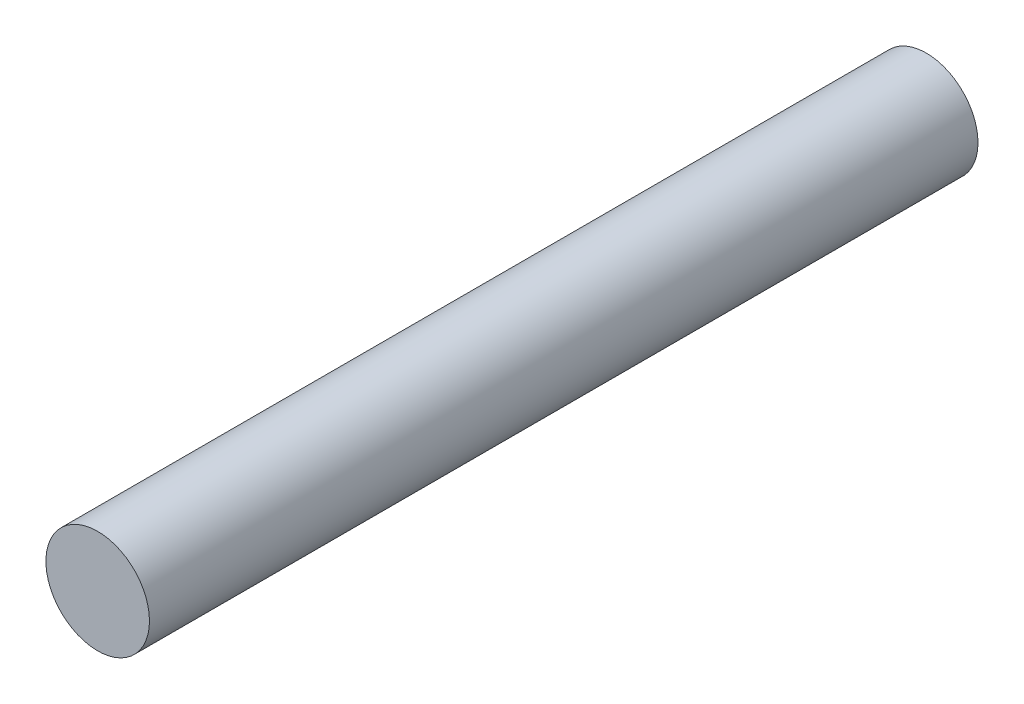
SolidWorks part; units mm, degrees
ref_plane "Front Plane" through (0, 0, 0) normal (0, 0, 1) x (1, 0, 0)
ref_plane "Top Plane" through (0, 0, 0) normal (0, 1, 0) x (1, 0, 0)
ref_plane "Right Plane" through (0, 0, 0) normal (1, 0, 0) x (0, 0, -1)
other "Default"
sketch "Sketch1" plane through (0, 0, 0) normal (0, 0, 1) x (1, 0, 0)
  circle A0 centre (0, 0) radius 2.5
  dimension "Diameter" = 5
extrude "Boss-Extrude1" add sketch "Sketch1" along normal mid plane 40
